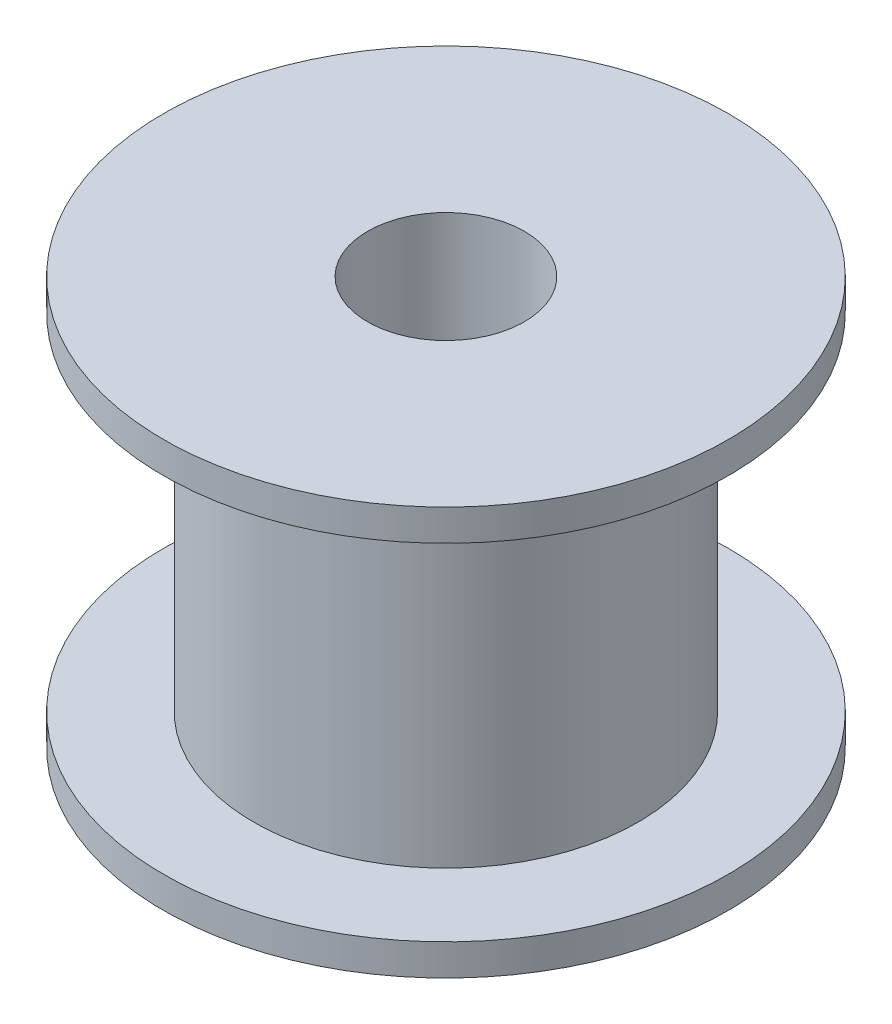
SolidWorks part; units mm, degrees
ref_plane "Front Plane" through (0, 0, 0) normal (0, 0, 1) x (1, 0, 0)
ref_plane "Top Plane" through (0, 0, 0) normal (0, 1, 0) x (1, 0, 0)
ref_plane "Right Plane" through (0, 0, 0) normal (1, 0, 0) x (0, 0, -1)
sketch "Sketch1" plane through (0, 0, 0) normal (0, 0, 1) x (1, 0, 0)
  line L0 (0, 0) -> (0, 13) construction
  line L1 (2.5, 0) -> (2.5, 13)
  line L2 (2.5, 13) -> (9, 13)
  line L3 (9, 13) -> (9, 12)
  line L4 (9, 12) -> (6.125, 12)
  line L5 (6.125, 12) -> (6.125, 1)
  line L6 (6.125, 1) -> (9, 1)
  line L7 (9, 1) -> (9, 0)
  line L8 (9, 0) -> (2.5, 0)
  dimension "D1" = 13
  dimension "D2" = 1
  dimension "D3" = 12.25
  dimension "D4" = 18
  dimension "D5" = 5
revolve "Revolve1" add sketch "Sketch1" angle 360 about L0
ref_plane "belt_mid" through (0, 6.5, 0) normal (0, 1, 0) x (1, 0, 0)
